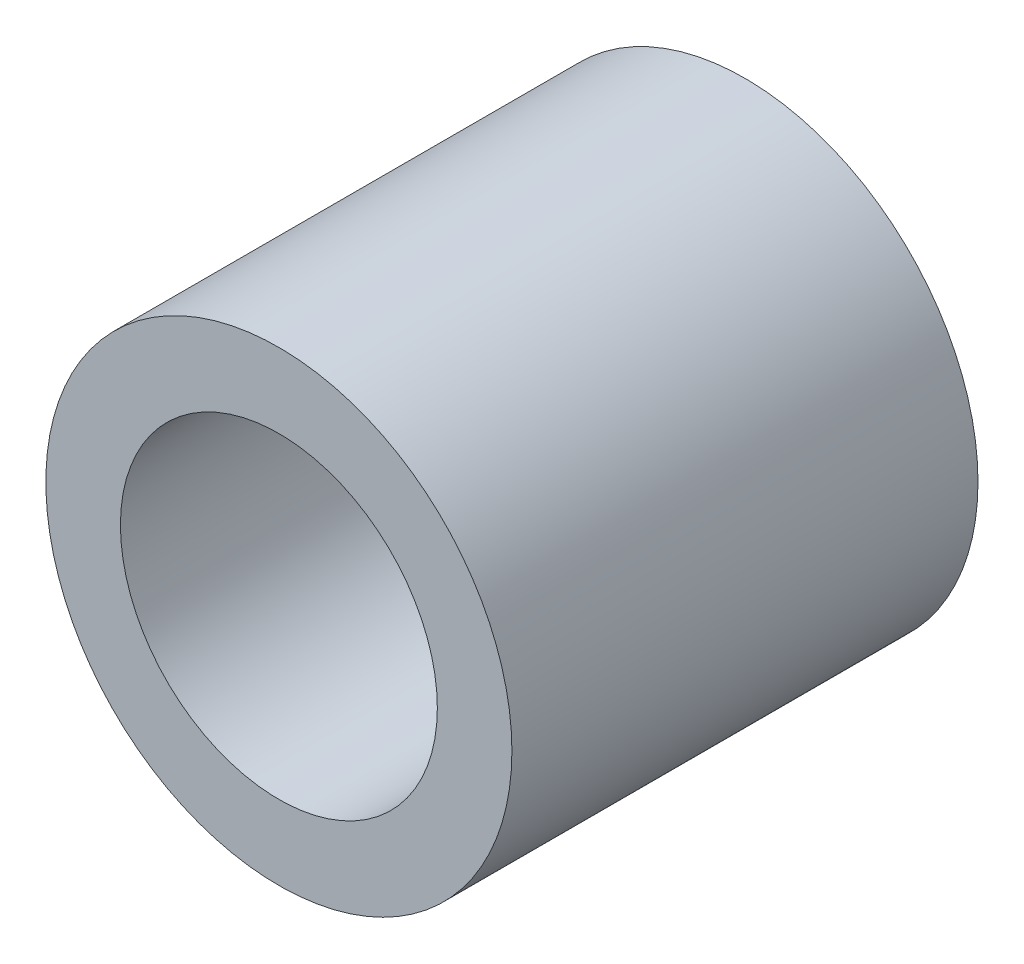
SolidWorks part; units mm, degrees
ref_plane "正面" through (0, 0, 0) normal (0, 0, 1) x (1, 0, 0)
ref_plane "平面" through (0, 0, 0) normal (0, 1, 0) x (1, 0, 0)
ref_plane "右側面" through (0, 0, 0) normal (1, 0, 0) x (0, 0, -1)
sketch "ｽｹｯﾁ1" plane through (0, 0, 0) normal (0, 0, 1) x (1, 0, 0)
  circle A0 centre (-0.9621, 1.4455) radius 1.7
  circle A1 centre (-0.9621, 1.4455) radius 2.5
  dimension "D1" = 3.4
  dimension "D2" = 5
extrude "ﾎﾞｽ - 押し出し1" add sketch "ｽｹｯﾁ1" along normal blind 5
